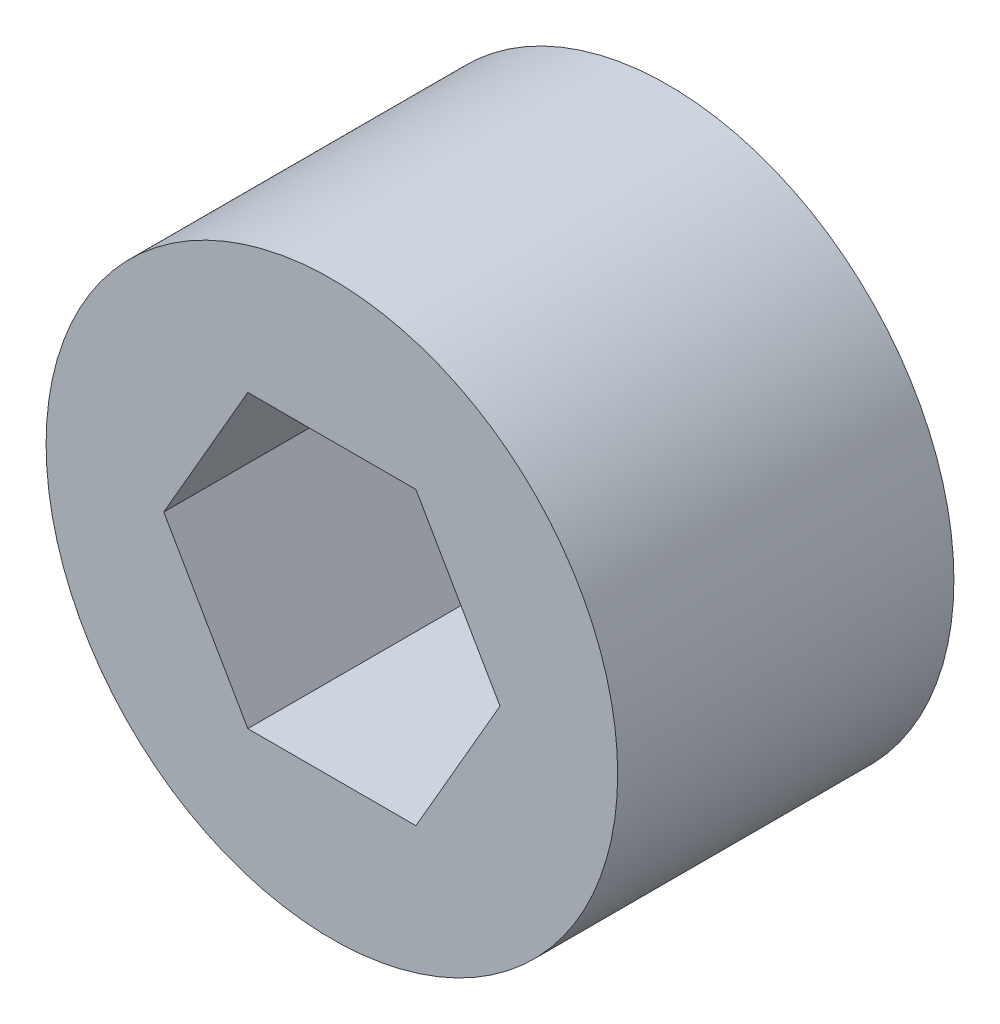
SolidWorks part; units mm, degrees
ref_plane "前视基准面" through (0, 0, 0) normal (0, 0, 1) x (1, 0, 0)
ref_plane "上视基准面" through (0, 0, 0) normal (0, 1, 0) x (1, 0, 0)
ref_plane "右视基准面" through (0, 0, 0) normal (1, 0, 0) x (0, 0, -1)
sketch "草图1" plane through (0, 0, 0) normal (0, 0, 1) x (1, 0, 0)
  line L1 (2.5, -4.3301) -> (5, 0)
  line L2 (5, 0) -> (2.5, 4.3301)
  line L3 (2.5, 4.3301) -> (-2.5, 4.3301)
  line L4 (-2.5, 4.3301) -> (-5, 0)
  line L5 (-5, 0) -> (-2.5, -4.3301)
  line L6 (-2.5, -4.3301) -> (2.5, -4.3301)
  circle A0 centre (0, 0) radius 8.5
  circle A1 centre (0, 0) radius 5 construction
  dimension "D1" = 17
  dimension "D2" = 10
extrude "凸台-拉伸1" add sketch "草图1" along normal blind 10
